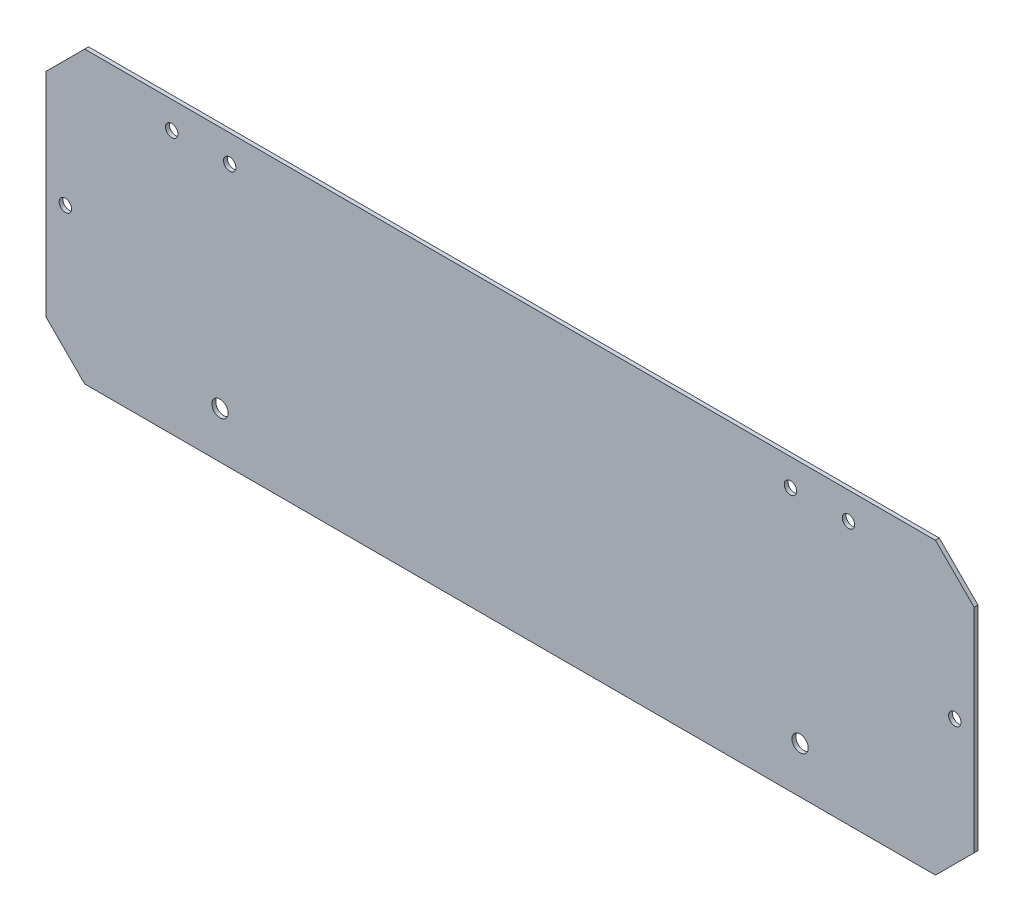
SolidWorks part; units mm, degrees
ref_plane "前视基准面" through (0, 0, 0) normal (0, 0, 1) x (1, 0, 0)
ref_plane "上视基准面" through (0, 0, 0) normal (0, 1, 0) x (1, 0, 0)
ref_plane "右视基准面" through (0, 0, 0) normal (1, 0, 0) x (0, 0, -1)
sketch "草图1" plane through (0, 0, 0) normal (0, 0, 1) x (1, 0, 0)
  line L0 (120, 0) -> (120, -120) construction
  line L1 (0, 0) -> (240, 0)
  line L2 (0, 0) -> (0, 75)
  line L3 (0, 75) -> (240, 75)
  line L4 (240, 0) -> (240, 75)
  line L5 (120, -120) -> (0, 0) construction
  line L6 (120, -120) -> (240, 0) construction
  line L7 (120, 75) -> (120, 0) construction
  dimension "D1" = 240
  dimension "D2" = 75
extrude "凸台-拉伸1" add sketch "草图1" along normal blind 1
chamfer "倒角1" distance 10 angle 45 4 edges at (240, 75, 0.5) (240, 0, 0.5) (0, 0, 0.5) (0, 75, 0.5)
sketch "草图3" plane through (0, 0, 0) normal (0, 0, -1) x (-1, 0, 0)
  line L0 (-120, 0) -> (-120, 75) construction
  line L1 (-10, 0) -> (-230, 0) construction
  line L2 (-230, 75) -> (-10, 75) construction
  line L4 (-100, 25) -> (-110, 42.3205)
  line L5 (-110, 42.3205) -> (-130, 42.3205)
  line L6 (-130, 42.3205) -> (-140, 25)
  line L7 (-140, 25) -> (-130, 7.6795)
  line L8 (-130, 7.6795) -> (-110, 7.6795)
  line L9 (-110, 7.6795) -> (-100, 25)
  circle A0 centre (-120, 25) radius 17.3205 construction
  dimension "D1" = 20
  dimension "D2" = 25
sketch "草图4" plane through (0, 0, 0) normal (0, 0, -1) x (-1, 0, 0)
  line L0 (-120, 75) -> (-120, 45) construction
  line L1 (-230, 75) -> (-10, 75) construction
  line L2 (-195, 12) -> (-45, 12) construction
  line L3 (-120, 12) -> (-120, 0) construction
  line L4 (-10, 0) -> (-230, 0) construction
  line L5 (-207.5, 68) -> (-192.5, 68) construction
  line L6 (-200, 68) -> (-200, 75) construction
  line L7 (-40, 68) -> (-40, 75) construction
  line L8 (-32.5, 68) -> (-47.5, 68) construction
  line L9 (-235, 37.5) -> (-240, 37.5) construction
  line L10 (-240, 10) -> (-240, 65) construction
  line L11 (-5, 37.5) -> (0, 37.5) construction
  line L12 (0, 65) -> (0, 10) construction
  circle A0 centre (-195, 12) radius 2.1
  circle A1 centre (-45, 12) radius 2.1
  circle A2 centre (-207.5, 68) radius 1.6
  circle A3 centre (-192.5, 68) radius 1.6
  circle A4 centre (-47.5, 68) radius 1.6
  circle A5 centre (-32.5, 68) radius 1.6
  circle A6 centre (-235, 37.5) radius 1.6
  circle A7 centre (-5, 37.5) radius 1.6
  dimension "D2" = 4.2
  dimension "D5" = 3.2
  dimension "D10" = 3.2
  dimension "D12" = 3.2
  dimension "D1" = 30
  dimension "D3" = 12
  dimension "D4" = 150
  dimension "D6" = 7
  dimension "D7" = 80
  dimension "D8" = 15
  dimension "D9" = 5
  dimension "D11" = 5
extrude "切除-拉伸3" cut sketch "草图4" against normal blind 10
